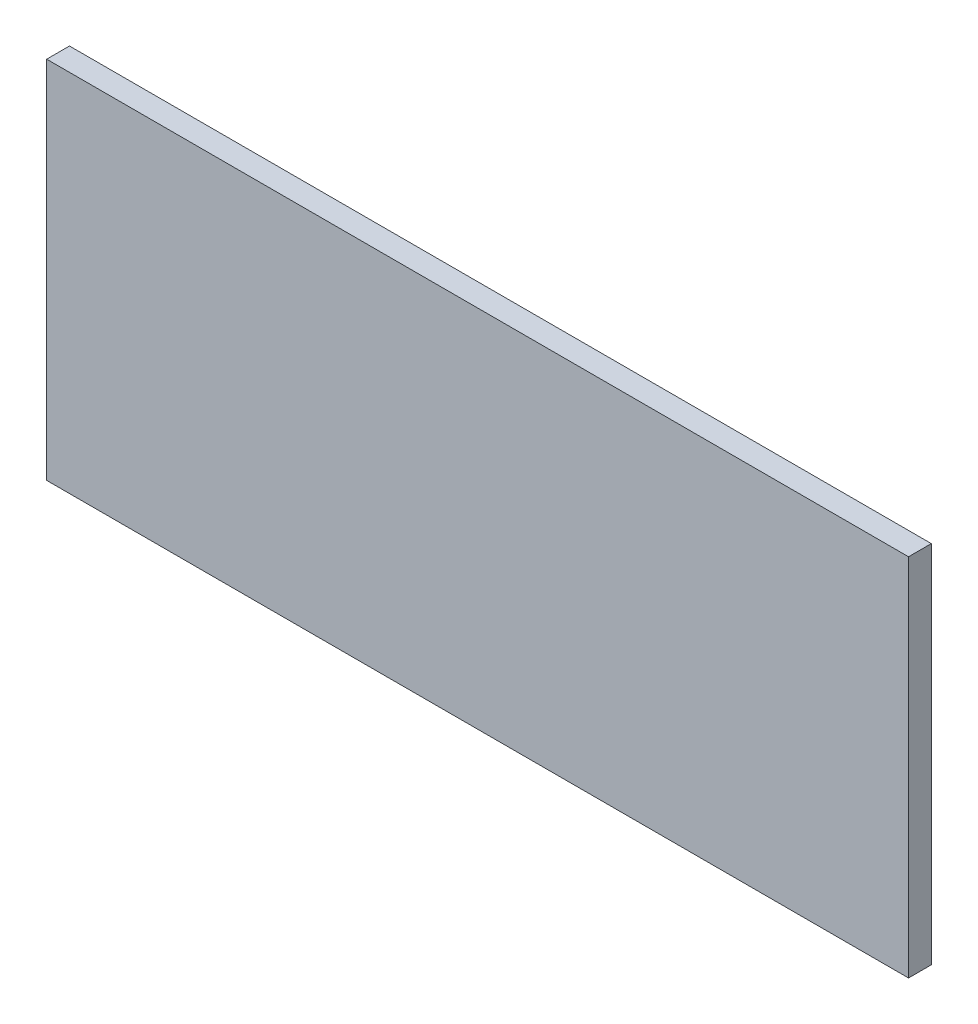
SolidWorks part; units mm, degrees
ref_plane "Front Plane" through (0, 0, 0) normal (0, 0, 1) x (1, 0, 0)
ref_plane "Top Plane" through (0, 0, 0) normal (0, 1, 0) x (1, 0, 0)
ref_plane "Right Plane" through (0, 0, 0) normal (1, 0, 0) x (0, 0, -1)
sketch "Sketch1" plane through (0, 0, 0) normal (0, 0, 1) x (1, 0, 0)
  line L1 (-94.5, 40) -> (94.5, 40)
  line L2 (-94.5, 40) -> (-94.5, -40)
  line L3 (-94.5, -40) -> (94.5, -40)
  line L4 (94.5, 40) -> (94.5, -40)
  line L5 (-94.5, 40) -> (94.5, -40) construction
  line L6 (-94.5, -40) -> (94.5, 40) construction
  point P0 (0, 0)
  dimension "D1" = 80
  dimension "D2" = 189
extrude "Boss-Extrude1" add sketch "Sketch1" along normal blind 5
